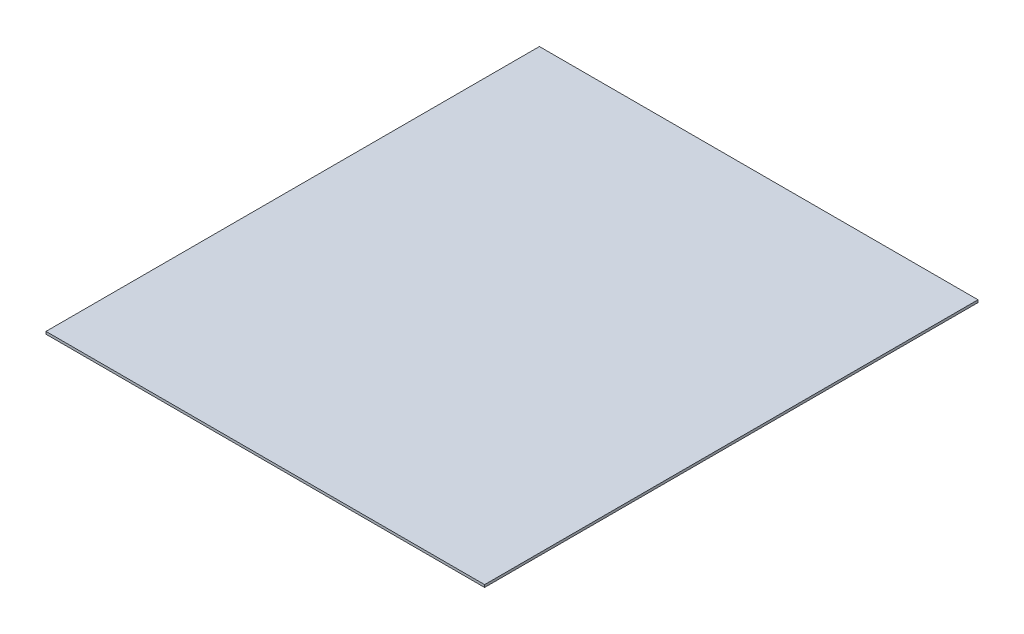
SolidWorks part; units mm, degrees
ref_plane "Alzado" through (0, 0, 0) normal (0, 0, 1) x (1, 0, 0)
ref_plane "Planta" through (0, 0, 0) normal (0, 1, 0) x (1, 0, 0)
ref_plane "Vista lateral" through (0, 0, 0) normal (1, 0, 0) x (0, 0, -1)
sketch "Croquis1" plane through (0, 0, 0) normal (0, 1, 0) x (1, 0, 0)
  line L1 (-560.475, -630.475) -> (560.475, -630.475)
  line L2 (-560.475, -630.475) -> (-560.475, 630.475)
  line L3 (-560.475, 630.475) -> (560.475, 630.475)
  line L4 (560.475, -630.475) -> (560.475, 630.475)
  line L5 (-560.475, -630.475) -> (560.475, 630.475) construction
  line L6 (-560.475, 630.475) -> (560.475, -630.475) construction
  point P0 (0, 0)
  dimension "D1" = 1120.95
  dimension "D2" = 1260.95
extrude "Saliente-Extruir1" add sketch "Croquis1" along normal blind 6.35
